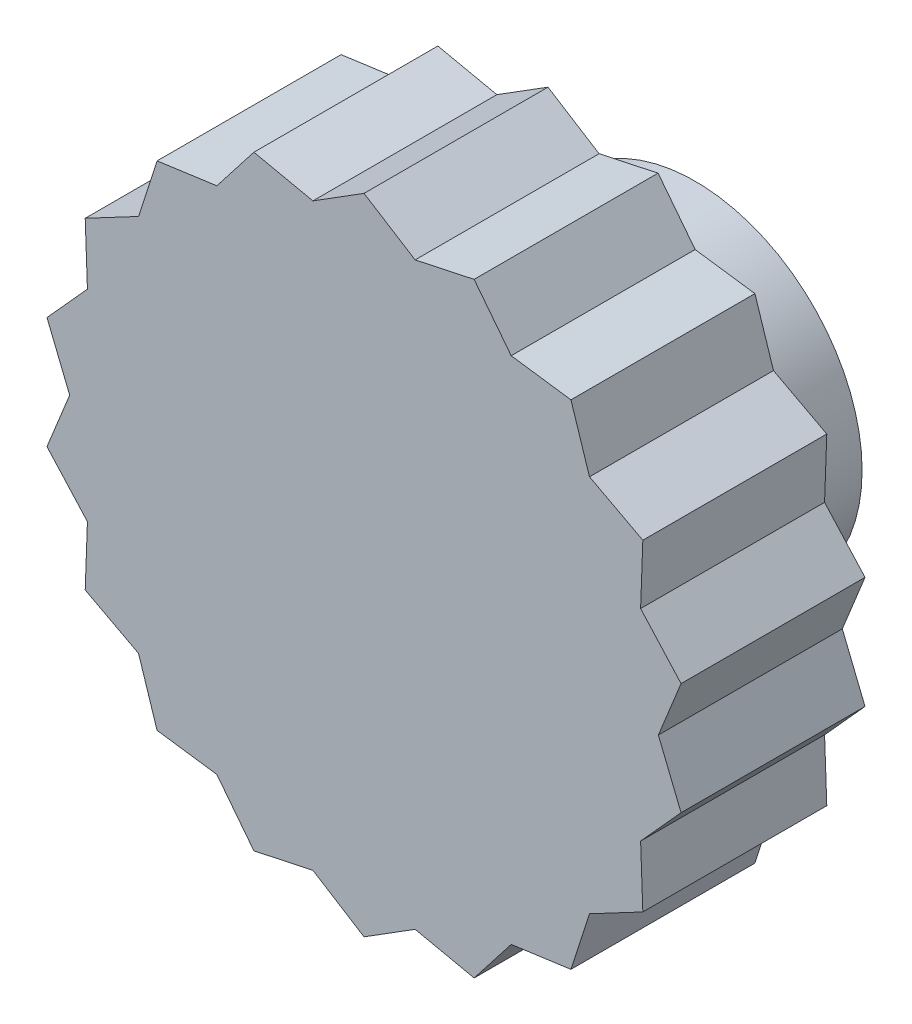
SolidWorks part; units mm, degrees
ref_plane "Alzado" through (0, 0, 0) normal (0, 0, 1) x (1, 0, 0)
ref_plane "Planta" through (0, 0, 0) normal (0, 1, 0) x (1, 0, 0)
ref_plane "Vista lateral" through (0, 0, 0) normal (1, 0, 0) x (0, 0, -1)
sketch "Croquis1" plane through (0, 0, 0) normal (0, 0, 1) x (1, 0, 0)
  circle A0 centre (0, 0) radius 17.5
  dimension "D1" = 35
extrude "Saliente-Extruir1" add sketch "Croquis1" along normal blind 10
sketch "Croquis2" plane through (0, 0, 0) normal (0, 0, -1) x (-1, 0, 0)
  circle A0 centre (0, 0) radius 9.075
  circle A1 centre (0, 0) radius 4.075
  dimension "D1" = 8.15
  dimension "D2" = 5
extrude "Saliente-Extruir2" add sketch "Croquis2" along normal blind 8
sketch "Croquis3" plane through (0, 0, 10) normal (0, 0, 1) x (1, 0, 0)
  line L0 (0, 17.5) -> (0, 0) construction
  line L1 (2.7784, 15.7569) -> (0, 0) construction
  line L2 (0, 17.5) -> (2.7784, 15.7569)
  line L3 (2.7784, 15.7569) -> (5.9854, 16.4446)
  line L4 (8, 13.8564) -> (11.2488, 13.4058)
  line L5 (5.9854, 16.4446) -> (8, 13.8564)
  line L6 (12.2567, 10.2846) -> (15.1554, 8.75)
  line L7 (11.2488, 13.4058) -> (12.2567, 10.2846)
  line L8 (15.0351, 5.4723) -> (17.2341, 3.0388)
  line L9 (15.1554, 8.75) -> (15.0351, 5.4723)
  line L10 (16, 0) -> (17.2341, -3.0388)
  line L11 (17.2341, 3.0388) -> (16, 0)
  line L12 (15.0351, -5.4723) -> (15.1554, -8.75)
  line L13 (17.2341, -3.0388) -> (15.0351, -5.4723)
  line L14 (12.2567, -10.2846) -> (11.2488, -13.4058)
  line L15 (15.1554, -8.75) -> (12.2567, -10.2846)
  line L16 (8, -13.8564) -> (5.9854, -16.4446)
  line L17 (11.2488, -13.4058) -> (8, -13.8564)
  line L18 (2.7784, -15.7569) -> (0, -17.5)
  line L19 (5.9854, -16.4446) -> (2.7784, -15.7569)
  line L20 (-2.7784, -15.7569) -> (-5.9854, -16.4446)
  line L21 (0, -17.5) -> (-2.7784, -15.7569)
  line L22 (-8, -13.8564) -> (-11.2488, -13.4058)
  line L23 (-5.9854, -16.4446) -> (-8, -13.8564)
  line L24 (-12.2567, -10.2846) -> (-15.1554, -8.75)
  line L25 (-11.2488, -13.4058) -> (-12.2567, -10.2846)
  line L26 (-15.0351, -5.4723) -> (-17.2341, -3.0388)
  line L27 (-15.1554, -8.75) -> (-15.0351, -5.4723)
  line L28 (-16, 0) -> (-17.2341, 3.0388)
  line L29 (-17.2341, -3.0388) -> (-16, 0)
  line L30 (-15.0351, 5.4723) -> (-15.1554, 8.75)
  line L31 (-17.2341, 3.0388) -> (-15.0351, 5.4723)
  line L32 (-12.2567, 10.2846) -> (-11.2488, 13.4058)
  line L33 (-15.1554, 8.75) -> (-12.2567, 10.2846)
  line L34 (-8, 13.8564) -> (-5.9854, 16.4446)
  line L35 (-11.2488, 13.4058) -> (-8, 13.8564)
  line L36 (-2.7784, 15.7569) -> (0, 17.5)
  line L37 (-5.9854, 16.4446) -> (-2.7784, 15.7569)
  circle A0 centre (0, 0) radius 17.5 construction
  circle A2 centre (0, 0) radius 19
  point P62 (0, 0)
  dimension "D4" = 38
  dimension "D1" = 10
  dimension "D2" = 16
  dimension "D3" = 18
extrude "Cortar-Extruir1" cut sketch "Croquis3" against normal up to next
sketch "Croquis4" plane through (0, 0, 0) normal (0, 1, 0) x (1, 0, 0)
  line L0 (0, 0) -> (0, 8) construction
  line L1 (9.075, 8) -> (-9.075, 8) construction
  circle A1 centre (0, 3.75) radius 2.05
  dimension "D2" = 4.1
  dimension "D1" = 4.25
extrude "Cortar-Extruir2" cut sketch "Croquis4" against normal through all both and the other way through all
sketch "Croquis5" plane through (0, 0, 0) normal (0, 0, -1) x (-1, 0, 0)
  circle A1 centre (0, 0) radius 4.075
  circle A2 centre (0, 0) radius 4.075
  dimension "D1" = 0
extrude "Cortar-Extruir3" cut sketch "Croquis5" against normal blind 5
